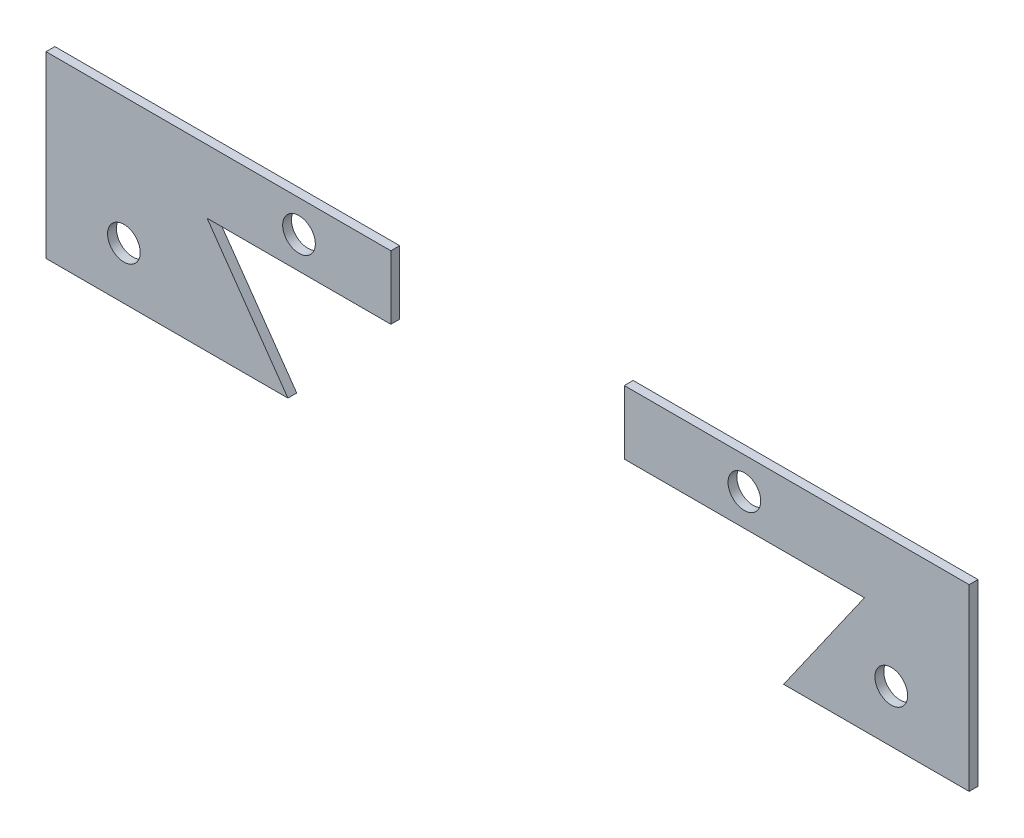
SolidWorks part; units mm, degrees
material "Plain Carbon Steel"
ref_plane "Front Plane" through (0, 0, 0) normal (0, 0, 1) x (1, 0, 0)
ref_plane "Top Plane" through (0, 0, 0) normal (0, 1, 0) x (1, 0, 0)
ref_plane "Right Plane" through (0, 0, 0) normal (1, 0, 0) x (0, 0, -1)
sketch "Sketch1" plane through (0, 0, 0) normal (0, 0, 1) x (1, 0, 0)
  line L12 (0, 25.4) -> (47.4437, 25.4)
  line L13 (47.4437, 25.4) -> (47.4437, 16.637)
  line L14 (47.4437, 15.875) -> (47.4437, 25.4) construction
  line L15 (47.4437, 16.637) -> (22.1631, 16.637)
  line L16 (22.1631, 16.637) -> (33.2789, 0.762)
  line L17 (33.2789, 0.762) -> (0, 0.762)
  line L18 (0, 25.4) -> (0, 0) construction
  line L19 (0, 0.762) -> (0, 25.4)
  line L20 (0, 0) -> (34.7427, 0) construction
  line L22 (23.6269, 15.875) -> (47.4437, 15.875) construction
  line L23 (34.7427, 0) -> (23.6269, 15.875) construction
  line L24 (79.5563, 25.4) -> (127, 25.4)
  line L25 (127, 25.4) -> (127, 0.762)
  line L26 (127, 0.762) -> (101.473, 0.762)
  line L27 (101.473, 0.762) -> (112.5888, 16.637)
  line L28 (112.5888, 16.637) -> (79.5563, 16.637)
  line L29 (79.5563, 25.4) -> (79.5563, 15.875) construction
  line L30 (79.5563, 16.637) -> (79.5563, 25.4)
  line L31 (111.125, 15.875) -> (100.0092, 0) construction
  line L32 (100.0092, 0) -> (127, 0) construction
  dimension "D1" = 0.762
  dimension "D2" = 0.762
  dimension "D3" = 0.762
  dimension "D4" = 0.762
  dimension "D5" = 0.762
extrude "Boss-Extrude1" add sketch "Sketch1" along normal blind 1.2141
hole_wizard "#8 Clearance Hole1" positions "Sketch2" profile "Sketch3" hole size "#8" standard "ANSI Inch" end condition through all
sketch "Sketch2" plane through (0, -15.875, 1.2141) normal (0, 0, 1) x (1, 0, 0)
  line L0 (34.8034, 41.275) -> (34.8034, 32.512) construction
  line L3 (96.0726, 41.275) -> (96.0726, 32.512) construction
  line L6 (111.125, 31.75) -> (127, 31.75) construction
  line L7 (15.875, 31.75) -> (0, 31.75) construction
  line L8 (7.9375, 31.75) -> (13.4954, 15.875) construction
  line L9 (119.0625, 31.75) -> (113.5046, 15.875) construction
  line L22 (127, 44.45) -> (0, 44.45) construction
  line L23 (0, 44.45) -> (0, 15.875) construction
  line L24 (0, 15.875) -> (26.9908, 15.875) construction
  line L25 (26.9908, 15.875) -> (15.875, 31.75) construction
  line L26 (15.875, 31.75) -> (111.125, 31.75) construction
  line L27 (111.125, 31.75) -> (100.0092, 15.875) construction
  line L28 (100.0092, 15.875) -> (127, 15.875) construction
  line L29 (127, 15.875) -> (127, 44.45) construction
  point P0 (10.7164, 23.8125)
  point P1 (34.8034, 36.8935)
  point P2 (96.0726, 36.8935)
  point P3 (116.2836, 23.8125)
sketch "Sketch3" plane through (10.7164, 7.9375, 1.2141) normal (1, 0, 0) x (0, -1, 0)
  line L0 (0, 0) -> (0, 1.2141)
  line L1 (0, 1.2141) -> (2.2479, 1.2141)
  line L2 (2.2479, 1.2141) -> (2.2479, 0)
  line L3 (2.2479, 0) -> (0, 0)
  line L4 (0, -6.35) -> (0, 107.95) construction
  dimension "Thru Hole Dia." = 4.4958
  dimension "Thru Hole Depth" = 1.2141
equation "\"dovetail-angle\"= 55"
equation "\"dovetail-stock-width\"= 5"
equation "\"dovetail-stock-height\"= 1.25"
equation "\"dovetail-depth\"= 0.5 * \"dovetail-stock-height\""
equation "\"dovetail-throat-width\"= \"dovetail-stock-width\" - (2 * \"dovetail-depth\")"
equation "\"delta-x\"= 6"
equation "\"delta-y\"= 3"
equation "\"gib-thickness\"= 0.25"
equation "\"x-slide-length\"= \"dovetail-stock-width\" + \"delta-x\""
equation "\"y-slide-length\"= \"dovetail-stock-width\" + \"delta-y\""
equation "\"dog-point-diam\"= .149"
equation "\"dog-point-length\"= .067"
equation "\"dovetail-double-height\"= 2 * \"dovetail-depth\" + 0.5"
equation "\"acme-major-diam\"= .5"
equation "\"acme-pitch-diam\"= 0.45"
equation "\"acme-minor-diam\"= 0.4"
equation "\"acme-nut-od\"= 1.47"
equation "\"acme-nut-length\"= 1"
equation "\"acme-nut-trim-height\"= .75"
equation "\"screw-bearing-od\"= 0.5"
equation "\"screw-bearing-length\"= .25"
equation "\"screw-bearing-id\"= .375"
equation "\"end-plate-thickness\"= \"screw-bearing-length\""
equation "\"screw-add-length\"= 2 * \"end-plate-thickness\" + 1 + 0.5"
equation "\"x-screw-length\"= \"x-slide-length\" + \"screw-add-length\""
equation "\"y-screw-length\"= \"y-slide-length\" + \"screw-add-length\""
equation "\"acme-nut-mount-hole-space-horz\"= 0.82"
equation "\"acme-nut-mount-hole-space-vert\"= 0.5 * \"acme-nut-length\""
equation "\"vise-hole-center-dist\"= 6.75"
equation "\"wiper_plate_clearance\"= .03"
equation "\"D1@Sketch1\"=\"wiper_plate_clearance\""
equation "\"D2@Sketch1\"=\"wiper_plate_clearance\""
equation "\"D3@Sketch1\"=\"wiper_plate_clearance\""
equation "\"D4@Sketch1\"=\"wiper_plate_clearance\""
equation "\"D5@Sketch1\"=\"wiper_plate_clearance\""
